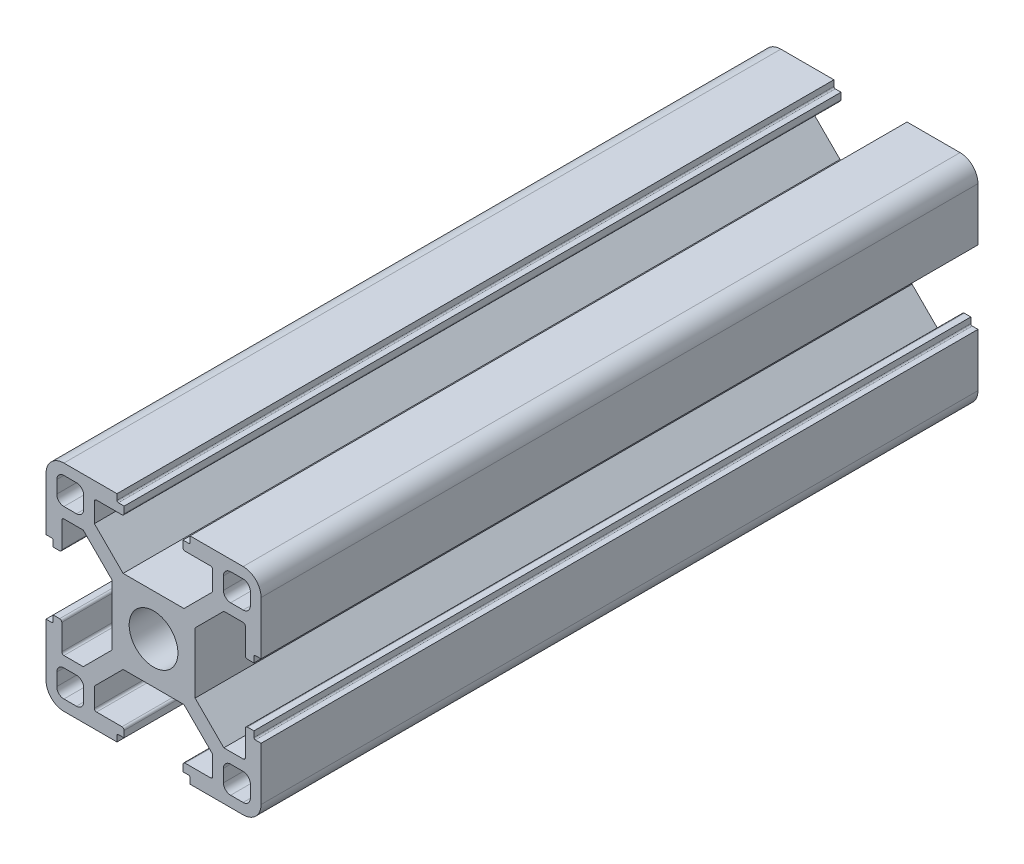
SolidWorks part; units mm, degrees
ref_plane "前视基准面" through (0, 0, 0) normal (0, 0, 1) x (1, 0, 0)
ref_plane "上视基准面" through (0, 0, 0) normal (0, 1, 0) x (1, 0, 0)
ref_plane "右视基准面" through (0, 0, 0) normal (1, 0, 0) x (0, 0, -1)
sketch "草图1" plane through (0, 0, 0) normal (0, 0, 1) x (1, 0, 0)
  line L0 (13.908, -22.0744) -> (15.658, -22.0744)
  line L1 (16.658, -23.0744) -> (16.658, -24.8244)
  line L2 (15.658, -25.8244) -> (13.908, -25.8244)
  line L3 (12.908, -24.8244) -> (12.908, -23.0744)
  line L4 (12.908, -1.5744) -> (12.908, 0.1756)
  line L5 (13.908, 1.1756) -> (15.658, 1.1756)
  line L6 (16.658, 0.1756) -> (16.658, -1.5744)
  line L7 (15.658, -2.5744) -> (13.908, -2.5744)
  line L8 (-6.592, -23.0744) -> (-6.592, -24.8244)
  line L9 (-7.592, -25.8244) -> (-9.342, -25.8244)
  line L10 (-10.342, -24.8244) -> (-10.342, -23.0744)
  line L11 (-9.342, -22.0744) -> (-7.592, -22.0744)
  line L12 (-7.592, -2.5744) -> (-9.342, -2.5744)
  line L13 (-10.342, -1.5744) -> (-10.342, 0.1756)
  line L14 (-9.342, 1.1756) -> (-7.592, 1.1756)
  line L15 (-6.592, 0.1756) -> (-6.592, -1.5744)
  line L16 (8.958, -8.0801) -> (12.9636, -4.0744)
  line L17 (12.9636, -4.0744) -> (15.658, -4.0744)
  line L18 (15.958, -4.3744) -> (15.958, -7.9244)
  line L19 (16.258, -8.2244) -> (17.158, -8.2244)
  line L20 (17.158, -8.2244) -> (17.158, -7.4244)
  line L21 (17.358, -7.2244) -> (18.158, -7.2244)
  line L22 (18.158, -7.2244) -> (18.158, 0.1756)
  line L23 (15.658, 2.6756) -> (8.258, 2.6756)
  line L24 (8.258, 2.6756) -> (8.258, 1.8756)
  line L25 (8.058, 1.6756) -> (7.258, 1.6756)
  line L26 (7.258, 1.6756) -> (7.258, 0.7756)
  line L27 (7.558, 0.4756) -> (11.108, 0.4756)
  line L28 (11.408, 0.1756) -> (11.408, -2.5188)
  line L29 (11.408, -2.5188) -> (7.4023, -6.5244)
  line L30 (7.4023, -6.5244) -> (-1.0864, -6.5244)
  line L31 (-1.0864, -6.5244) -> (-5.092, -2.5188)
  line L32 (-5.092, -2.5188) -> (-5.092, 0.1756)
  line L33 (-4.792, 0.4756) -> (-1.242, 0.4756)
  line L34 (-0.942, 0.7756) -> (-0.942, 1.6756)
  line L35 (-0.942, 1.6756) -> (-1.742, 1.6756)
  line L36 (-1.942, 1.8756) -> (-1.942, 2.6756)
  line L37 (-1.942, 2.6756) -> (-9.342, 2.6756)
  line L38 (-11.842, 0.1756) -> (-11.842, -7.2244)
  line L39 (-11.842, -7.2244) -> (-11.042, -7.2244)
  line L40 (-10.842, -7.4244) -> (-10.842, -8.2244)
  line L41 (-10.842, -8.2244) -> (-9.942, -8.2244)
  line L42 (-9.642, -7.9244) -> (-9.642, -4.3744)
  line L43 (-9.342, -4.0744) -> (-6.6477, -4.0744)
  line L44 (-6.6477, -4.0744) -> (-2.642, -8.0801)
  line L45 (-2.642, -8.0801) -> (-2.642, -16.5688)
  line L46 (-2.642, -16.5688) -> (-6.6477, -20.5744)
  line L47 (-6.6477, -20.5744) -> (-9.342, -20.5744)
  line L48 (-9.642, -20.2744) -> (-9.642, -16.7244)
  line L49 (-9.942, -16.4244) -> (-10.842, -16.4244)
  line L50 (-10.842, -16.4244) -> (-10.842, -17.2244)
  line L51 (-11.042, -17.4244) -> (-11.842, -17.4244)
  line L52 (-11.842, -17.4244) -> (-11.842, -24.8244)
  line L53 (-9.342, -27.3244) -> (-1.942, -27.3244)
  line L54 (-1.942, -27.3244) -> (-1.942, -26.5244)
  line L55 (-1.742, -26.3244) -> (-0.942, -26.3244)
  line L56 (-0.942, -26.3244) -> (-0.942, -25.4244)
  line L57 (-1.242, -25.1244) -> (-4.792, -25.1244)
  line L58 (-5.092, -24.8244) -> (-5.092, -22.1301)
  line L59 (-5.092, -22.1301) -> (-1.0864, -18.1244)
  line L60 (-1.0864, -18.1244) -> (7.4023, -18.1244)
  line L61 (7.4023, -18.1244) -> (11.408, -22.1301)
  line L62 (11.408, -22.1301) -> (11.408, -24.8244)
  line L63 (11.108, -25.1244) -> (7.558, -25.1244)
  line L64 (7.258, -25.4244) -> (7.258, -26.3244)
  line L65 (7.258, -26.3244) -> (8.058, -26.3244)
  line L66 (8.258, -26.5244) -> (8.258, -27.3244)
  line L67 (8.258, -27.3244) -> (15.658, -27.3244)
  line L68 (18.158, -24.8244) -> (18.158, -17.4244)
  line L69 (18.158, -17.4244) -> (17.358, -17.4244)
  line L70 (17.158, -17.2244) -> (17.158, -16.4244)
  line L71 (17.158, -16.4244) -> (16.258, -16.4244)
  line L72 (15.958, -16.7244) -> (15.958, -20.2744)
  line L73 (15.658, -20.5744) -> (12.9636, -20.5744)
  line L74 (12.9636, -20.5744) -> (8.958, -16.5688)
  line L75 (8.958, -16.5688) -> (8.958, -8.0801)
  arc A0 (16.658, -23.0744) -> (15.658, -22.0744) centre (15.658, -23.0744) ccw
  arc A1 (15.658, -25.8244) -> (16.658, -24.8244) centre (15.658, -24.8244) ccw
  arc A2 (12.908, -24.8244) -> (13.908, -25.8244) centre (13.908, -24.8244) ccw
  arc A3 (13.908, -22.0744) -> (12.908, -23.0744) centre (13.908, -23.0744) ccw
  arc A4 (13.908, 1.1756) -> (12.908, 0.1756) centre (13.908, 0.1756) ccw
  arc A5 (16.658, 0.1756) -> (15.658, 1.1756) centre (15.658, 0.1756) ccw
  arc A6 (15.658, -2.5744) -> (16.658, -1.5744) centre (15.658, -1.5744) ccw
  arc A7 (12.908, -1.5744) -> (13.908, -2.5744) centre (13.908, -1.5744) ccw
  arc A8 (-7.592, -25.8244) -> (-6.592, -24.8244) centre (-7.592, -24.8244) ccw
  arc A9 (-10.342, -24.8244) -> (-9.342, -25.8244) centre (-9.342, -24.8244) ccw
  arc A10 (-9.342, -22.0744) -> (-10.342, -23.0744) centre (-9.342, -23.0744) ccw
  arc A11 (-6.592, -23.0744) -> (-7.592, -22.0744) centre (-7.592, -23.0744) ccw
  arc A12 (-10.342, -1.5744) -> (-9.342, -2.5744) centre (-9.342, -1.5744) ccw
  arc A13 (-9.342, 1.1756) -> (-10.342, 0.1756) centre (-9.342, 0.1756) ccw
  arc A14 (-6.592, 0.1756) -> (-7.592, 1.1756) centre (-7.592, 0.1756) ccw
  arc A15 (-7.592, -2.5744) -> (-6.592, -1.5744) centre (-7.592, -1.5744) ccw
  circle A16 centre (3.158, -12.3244) radius 3.4
  arc A17 (15.958, -4.3744) -> (15.658, -4.0744) centre (15.658, -4.3744) ccw
  arc A18 (15.958, -7.9244) -> (16.258, -8.2244) centre (16.258, -7.9244) ccw
  arc A19 (17.358, -7.2244) -> (17.158, -7.4244) centre (17.358, -7.4244) ccw
  arc A20 (18.158, 0.1756) -> (15.658, 2.6756) centre (15.658, 0.1756) ccw
  arc A21 (8.058, 1.6756) -> (8.258, 1.8756) centre (8.058, 1.8756) ccw
  arc A22 (7.258, 0.7756) -> (7.558, 0.4756) centre (7.558, 0.7756) ccw
  arc A23 (11.408, 0.1756) -> (11.108, 0.4756) centre (11.108, 0.1756) ccw
  arc A24 (-4.792, 0.4756) -> (-5.092, 0.1756) centre (-4.792, 0.1756) ccw
  arc A25 (-1.242, 0.4756) -> (-0.942, 0.7756) centre (-1.242, 0.7756) ccw
  arc A26 (-1.942, 1.8756) -> (-1.742, 1.6756) centre (-1.742, 1.8756) ccw
  arc A27 (-9.342, 2.6756) -> (-11.842, 0.1756) centre (-9.342, 0.1756) ccw
  arc A28 (-10.842, -7.4244) -> (-11.042, -7.2244) centre (-11.042, -7.4244) ccw
  arc A29 (-9.942, -8.2244) -> (-9.642, -7.9244) centre (-9.942, -7.9244) ccw
  arc A30 (-9.342, -4.0744) -> (-9.642, -4.3744) centre (-9.342, -4.3744) ccw
  arc A31 (-9.642, -20.2744) -> (-9.342, -20.5744) centre (-9.342, -20.2744) ccw
  arc A32 (-9.642, -16.7244) -> (-9.942, -16.4244) centre (-9.942, -16.7244) ccw
  arc A33 (-11.042, -17.4244) -> (-10.842, -17.2244) centre (-11.042, -17.2244) ccw
  arc A34 (-11.842, -24.8244) -> (-9.342, -27.3244) centre (-9.342, -24.8244) ccw
  arc A35 (-1.742, -26.3244) -> (-1.942, -26.5244) centre (-1.742, -26.5244) ccw
  arc A36 (-0.942, -25.4244) -> (-1.242, -25.1244) centre (-1.242, -25.4244) ccw
  arc A37 (-5.092, -24.8244) -> (-4.792, -25.1244) centre (-4.792, -24.8244) ccw
  arc A38 (11.108, -25.1244) -> (11.408, -24.8244) centre (11.108, -24.8244) ccw
  arc A39 (7.558, -25.1244) -> (7.258, -25.4244) centre (7.558, -25.4244) ccw
  arc A40 (8.258, -26.5244) -> (8.058, -26.3244) centre (8.058, -26.5244) ccw
  arc A41 (15.658, -27.3244) -> (18.158, -24.8244) centre (15.658, -24.8244) ccw
  arc A42 (17.158, -17.2244) -> (17.358, -17.4244) centre (17.358, -17.2244) ccw
  arc A43 (16.258, -16.4244) -> (15.958, -16.7244) centre (16.258, -16.7244) ccw
  arc A44 (15.658, -20.5744) -> (15.958, -20.2744) centre (15.658, -20.2744) ccw
extrude "凸台-拉伸1" add sketch "草图1" along normal blind 100
